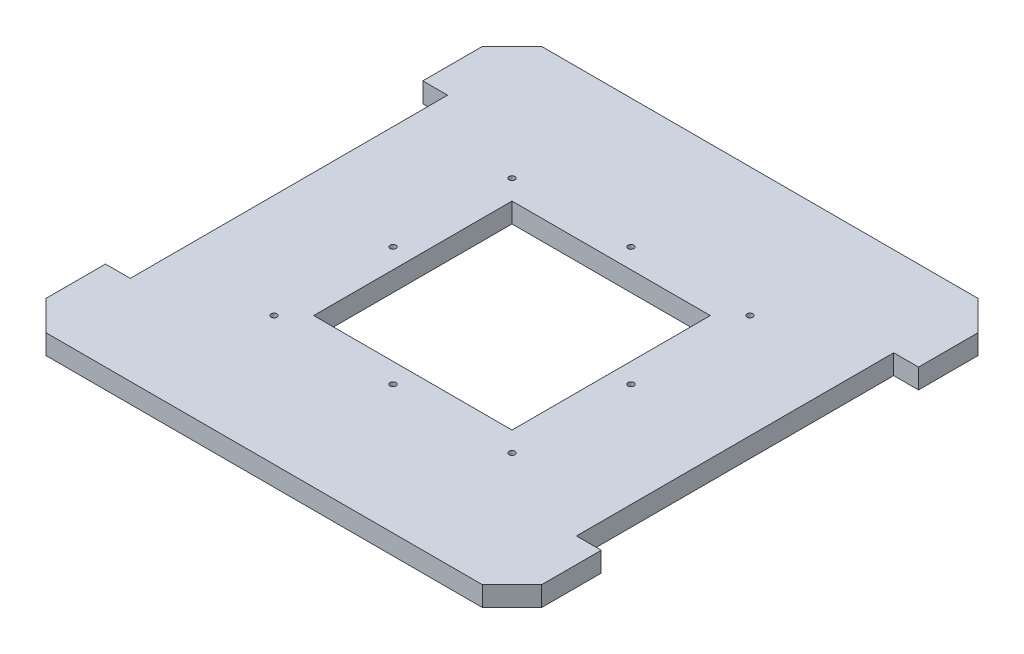
SolidWorks part; units mm, degrees
ref_plane "Alzado" through (0, 0, 0) normal (0, 0, 1) x (1, 0, 0)
ref_plane "Planta" through (0, 0, 0) normal (0, 1, 0) x (1, 0, 0)
ref_plane "Vista lateral" through (0, 0, 0) normal (1, 0, 0) x (0, 0, -1)
sketch "Croquis2" plane through (0, 0, 0) normal (0, 1, 0) x (1, 0, 0)
  line L0 (-62.5, 0) -> (62.5, 0) construction
  line L1 (0, -62.5) -> (0, 62.5) construction
  line L2 (-62.5, 0) -> (-62.5, 55)
  line L3 (-62.5, 55) -> (-55, 62.5)
  line L4 (-55, 62.5) -> (55, 62.5)
  line L5 (55, 62.5) -> (62.5, 55)
  line L6 (62.5, 55) -> (62.5, -55)
  line L7 (62.5, -55) -> (55, -62.5)
  line L8 (55, -62.5) -> (-55, -62.5)
  line L9 (-55, -62.5) -> (-62.5, -55)
  line L10 (-62.5, -55) -> (-62.5, 0)
  line L11 (-62.5, 55) -> (62.5, 55) construction
  line L12 (-55, 62.5) -> (-55, -62.5) construction
  line L14 (-25, 25) -> (25, 25)
  line L15 (-25, 25) -> (-25, -25)
  line L16 (-25, -25) -> (25, -25)
  line L17 (25, 25) -> (25, -25)
  line L18 (-25, 25) -> (25, -25) construction
  line L19 (-25, -25) -> (25, 25) construction
  line L20 (-30, -30) -> (30, -30) construction
  line L21 (-30, -30) -> (-30, 30) construction
  line L22 (-30, 30) -> (30, 30) construction
  line L23 (30, -30) -> (30, 30) construction
  line L24 (-30, -30) -> (30, 30) construction
  line L25 (-30, 30) -> (30, -30) construction
  circle A0 centre (30, 30) radius 0.75
  circle A1 centre (30, 0) radius 0.75
  circle A2 centre (30, -30) radius 0.75
  circle A3 centre (-30, -30) radius 0.75
  circle A4 centre (0, -30) radius 0.75
  circle A5 centre (-30, 0) radius 0.75
  circle A6 centre (-30, 30) radius 0.75
  circle A7 centre (0, 30) radius 0.75
  point P6 (0, 0)
  point P8 (0, 0)
  point P14 (0, 0)
  point P17 (0, 0)
  dimension "D5" = 1.5
  dimension "D1" = 110
  dimension "D2" = 125
  dimension "D3" = 50
  dimension "D4" = 60
extrude "Saliente-Extruir1" add sketch "Croquis2" along normal blind 5
sketch "Croquis3" plane through (0, 5, 0) normal (0, 1, 0) x (1, 0, 0)
  line L0 (62.5, -55) -> (62.5, 55) construction
  line L1 (62.5, -40) -> (56.25, -40)
  line L2 (62.5, -40) -> (62.5, 40)
  line L3 (62.5, 40) -> (56.25, 40)
  line L4 (56.25, -40) -> (56.25, 40)
  line L5 (30, 0) -> (56.25, 0) construction
  line L6 (0, 0) -> (0, 25) construction
  line L7 (25, 25) -> (-25, 25) construction
  line L8 (-62.5, 40) -> (-56.25, 40)
  line L9 (-56.25, -40) -> (-56.25, 40)
  line L10 (-62.5, -40) -> (-56.25, -40)
  line L11 (-62.5, -40) -> (-62.5, 40)
  dimension "D1" = 80
  dimension "D2" = 6.25
extrude "Cortar-Extruir1" cut sketch "Croquis3" against normal blind 5
